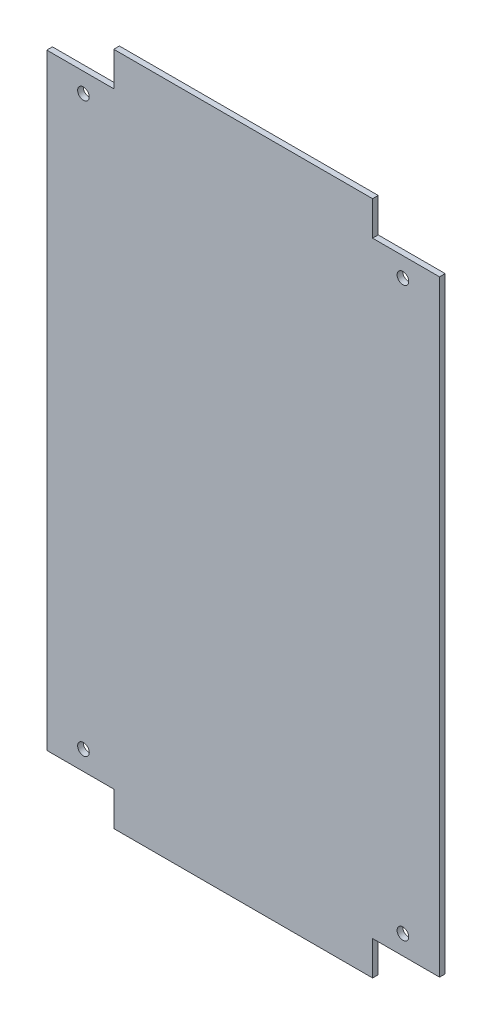
SolidWorks part; units mm, degrees
ref_plane "Front Plane" through (0, 0, 0) normal (0, 0, 1) x (1, 0, 0)
ref_plane "Top Plane" through (0, 0, 0) normal (0, 1, 0) x (1, 0, 0)
ref_plane "Right Plane" through (0, 0, 0) normal (1, 0, 0) x (0, 0, -1)
sketch "Sketch2" plane through (0, 0, 0) normal (0, 0, 1) x (1, 0, 0)
  line L0 (5193.5738, 1803.2371) -> (5212.5738, 1803.2371)
  line L1 (5212.5738, 1803.2371) -> (5212.5738, 1812.9371)
  line L2 (5212.5738, 1812.9371) -> (5285.9738, 1812.9371)
  line L3 (5285.9738, 1812.9371) -> (5285.9738, 1803.2371)
  line L4 (5285.9738, 1803.2371) -> (5304.9738, 1803.2371)
  line L5 (5304.9738, 1803.2371) -> (5304.9738, 1631.2371)
  line L6 (5304.9738, 1631.2371) -> (5285.9738, 1631.2371)
  line L7 (5285.9738, 1631.2371) -> (5285.9738, 1621.5371)
  line L8 (5285.9738, 1621.5371) -> (5212.5738, 1621.5371)
  line L9 (5212.5738, 1621.5371) -> (5212.5738, 1631.2371)
  line L10 (5212.5738, 1631.2371) -> (5193.5738, 1631.2371)
  line L11 (5193.5738, 1631.2371) -> (5193.5738, 1803.2371)
  line L14 (5249.2738, 1818.1623) -> (5249.2738, 1616.3118) construction
  line L15 (5303.2738, 1818.1623) -> (5195.2738, 1818.1623) construction
  line L16 (5195.2738, 1616.3118) -> (5303.2738, 1616.3118) construction
  line L17 (5189.2737, 1717.2371) -> (5309.274, 1717.2371) construction
  line L18 (5309.274, 1811.2371) -> (5309.274, 1623.2371) construction
  point P11 (5249.2738, 1812.9371)
  point P15 (5193.5738, 1717.2371)
  point P25 (5249.2738, 1717.2371)
  point P26 (5304.9738, 1717.2371)
  dimension "D1" = 191.4
  dimension "D2" = 111.4
  dimension "D3" = 73.4
  dimension "D4" = 172
extrude "Boss-Extrude1" add sketch "Sketch2" along normal blind 1.6
sketch "Sketch3" plane through (0, 0, 1.6) normal (0, 0, 1) x (1, 0, 0)
  arc A0 (5202.7238, 1797.7369) -> (5205.2238, 1797.7369) centre (5203.9738, 1797.7369) ccw construction
  arc A1 (5205.2238, 1797.7369) -> (5202.7238, 1797.7369) centre (5203.9738, 1797.7369) ccw construction
  arc A2 (5202.7238, 1797.7369) -> (5205.2238, 1797.7369) centre (5203.9738, 1797.7369) ccw construction
  arc A3 (5205.2238, 1797.7369) -> (5202.7238, 1797.7369) centre (5203.9738, 1797.7369) ccw construction
  arc A4 (5295.8238, 1797.7369) -> (5293.3238, 1797.7369) centre (5294.5738, 1797.7369) ccw construction
  arc A5 (5293.3238, 1797.7369) -> (5295.8238, 1797.7369) centre (5294.5738, 1797.7369) ccw construction
  arc A6 (5295.8238, 1797.7369) -> (5293.3238, 1797.7369) centre (5294.5738, 1797.7369) ccw construction
  arc A7 (5293.3238, 1797.7369) -> (5295.8238, 1797.7369) centre (5294.5738, 1797.7369) ccw construction
  arc A8 (5295.8238, 1636.7369) -> (5293.3238, 1636.7369) centre (5294.5738, 1636.7369) ccw construction
  arc A9 (5293.3238, 1636.7369) -> (5295.8238, 1636.7369) centre (5294.5738, 1636.7369) ccw construction
  arc A10 (5205.2238, 1636.7369) -> (5202.7238, 1636.7369) centre (5203.9738, 1636.7369) ccw construction
  arc A11 (5202.7238, 1636.7369) -> (5205.2238, 1636.7369) centre (5203.9738, 1636.7369) ccw construction
  arc A12 (5295.8238, 1636.7369) -> (5293.3238, 1636.7369) centre (5294.5738, 1636.7369) ccw construction
  arc A13 (5293.3238, 1636.7369) -> (5295.8238, 1636.7369) centre (5294.5738, 1636.7369) ccw construction
  arc A14 (5205.2238, 1636.7369) -> (5202.7238, 1636.7369) centre (5203.9738, 1636.7369) ccw construction
  arc A15 (5202.7238, 1636.7369) -> (5205.2238, 1636.7369) centre (5203.9738, 1636.7369) ccw construction
  arc A16 (5202.3238, 1797.7369) -> (5205.6238, 1797.7369) centre (5203.9738, 1797.7369) ccw
  arc A17 (5205.6238, 1797.7369) -> (5202.3238, 1797.7369) centre (5203.9738, 1797.7369) ccw
  arc A18 (5296.2238, 1797.7369) -> (5292.9238, 1797.7369) centre (5294.5738, 1797.7369) ccw
  arc A19 (5292.9238, 1797.7369) -> (5296.2238, 1797.7369) centre (5294.5738, 1797.7369) ccw
  arc A20 (5296.2238, 1636.7369) -> (5292.9238, 1636.7369) centre (5294.5738, 1636.7369) ccw
  arc A21 (5292.9238, 1636.7369) -> (5296.2238, 1636.7369) centre (5294.5738, 1636.7369) ccw
  arc A22 (5205.6238, 1636.7369) -> (5202.3238, 1636.7369) centre (5203.9738, 1636.7369) ccw
  arc A23 (5202.3238, 1636.7369) -> (5205.6238, 1636.7369) centre (5203.9738, 1636.7369) ccw
  dimension "D1" = 0.4
extrude "Cut-Extrude1" cut sketch "Sketch3" against normal blind 1.6
